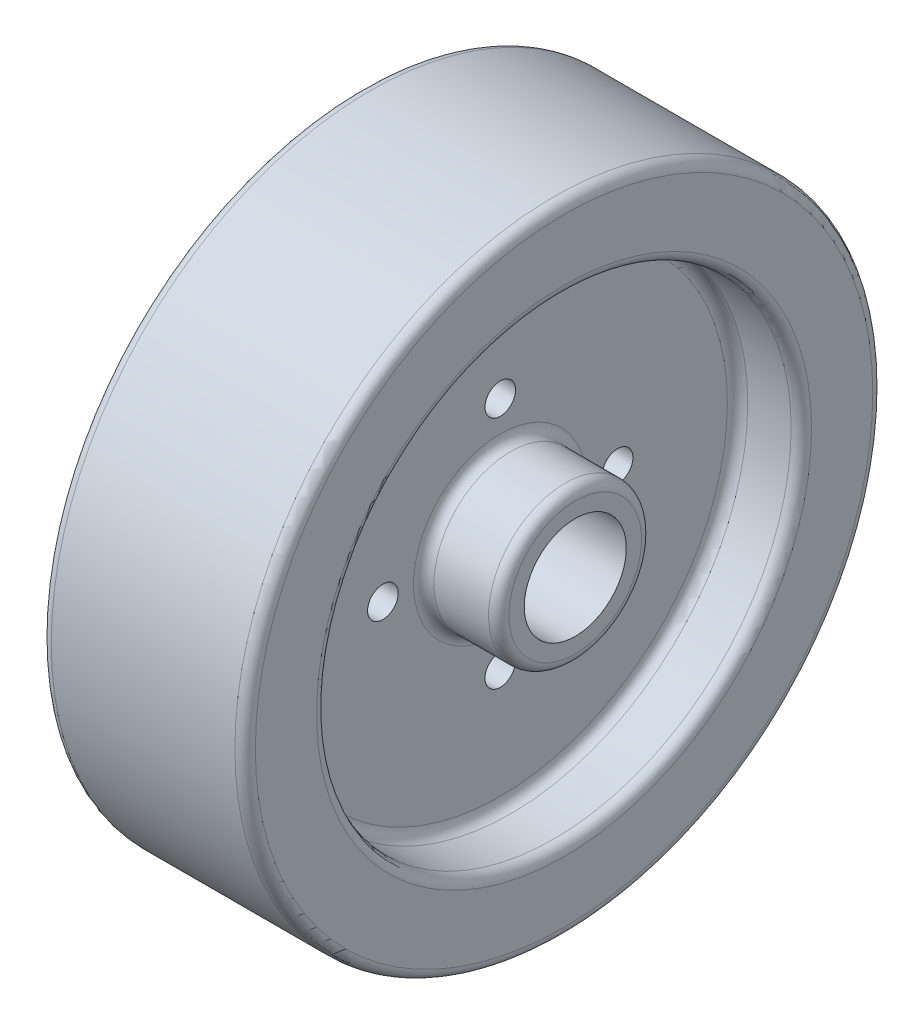
SolidWorks part; units mm, degrees
ref_plane "Front Plane" through (0, 0, 0) normal (0, 0, 1) x (1, 0, 0)
ref_plane "Top Plane" through (0, 0, 0) normal (0, 1, 0) x (1, 0, 0)
ref_plane "Right Plane" through (0, 0, 0) normal (1, 0, 0) x (0, 0, -1)
sketch "Sketch1" plane through (0, 0, 0) normal (0, 0, 1) x (1, 0, 0)
  line L0 (-20, -62.5) -> (20, -62.5)
  line L1 (20, -62.5) -> (20, -46.5)
  line L2 (20, -46.5) -> (7.5, -46.5)
  line L3 (7.5, -46.5) -> (7.5, -15)
  line L4 (7.5, -15) -> (22.2, -15)
  line L5 (22.2, -15) -> (22.2, -6)
  line L6 (0, -62.5) -> (0, 0) construction
  line L7 (0, 0) -> (22.2, 0) construction
  line L8 (22.2, -6) -> (-22.2, -6)
  line L9 (-22.2, -15) -> (-22.2, -6)
  line L10 (-7.5, -15) -> (-22.2, -15)
  line L11 (-7.5, -46.5) -> (-7.5, -15)
  line L12 (-20, -46.5) -> (-7.5, -46.5)
  line L13 (-20, -62.5) -> (-20, -46.5)
  point P12 (0, -6)
  dimension "D1" = 44.4
  dimension "D2" = 40
  dimension "D3" = 12
  dimension "D4" = 30
  dimension "D5" = 125
  dimension "D6" = 16
  dimension "D7" = 15
revolve "Revolve1" add sketch "Sketch1" angle 360 about L7
fillet "Fillet1" radius 2 10 edges at (7.5, 0, 46.5) (7.5, 0, 15) (-7.5, 0, 15) (-7.5, 0, 46.5) (-20, 0, 46.5) (20, 0, 46.5) (-20, 0, 62.5) (20, 0, 62.5) (22.2, 0, 15) (-22.2, 0, 15)
sketch "Sketch2" plane through (-22.2, 0, 0) normal (-1, 0, 0) x (0, 0, 1)
  circle A0 centre (0, 0) radius 10
  dimension "D1" = 20
extrude "centrebored out" cut sketch "Sketch2" against normal through all
sketch "Sketch3" plane through (-7.5, 0, 0) normal (-1, 0, 0) x (0, 0, 1)
  line L0 (0, 23) -> (0, 0) construction
  circle A0 centre (0, 23) radius 3
  circle A1 centre (23, 0) radius 3
  circle A2 centre (0, -23) radius 3
  circle A3 centre (-23, 0) radius 3
  point P13 (0, 0)
  dimension "D1" = 6
  dimension "D2" = 23
extrude "Cut-Extrude2" cut sketch "Sketch3" against normal blind 20
